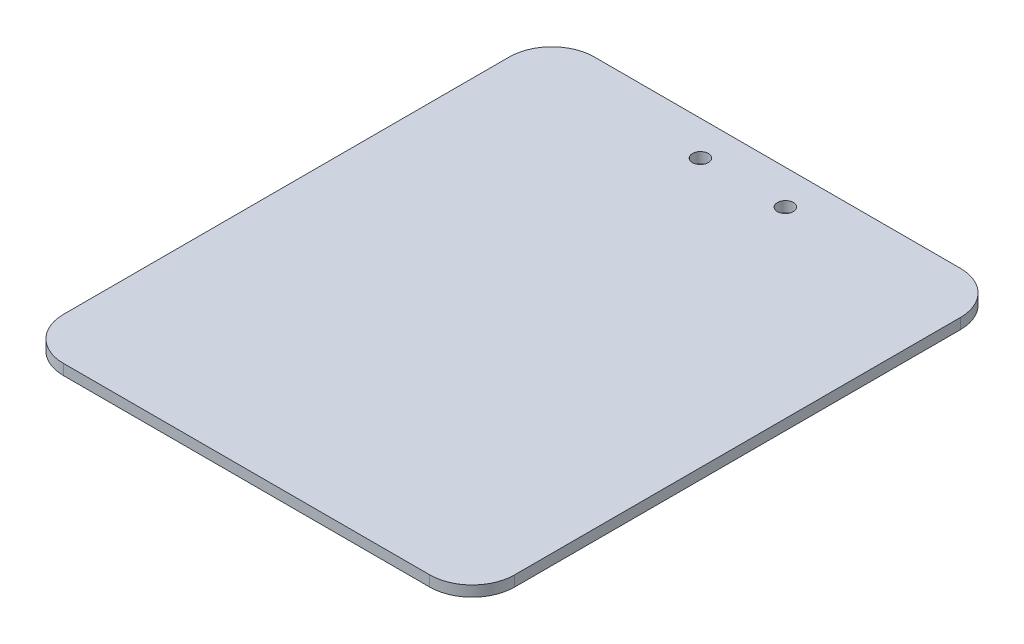
SolidWorks part; units mm, degrees
ref_plane "Front Plane" through (0, 0, 0) normal (0, 0, 1) x (1, 0, 0)
ref_plane "Top Plane" through (0, 0, 0) normal (0, 1, 0) x (1, 0, 0)
ref_plane "Right Plane" through (0, 0, 0) normal (1, 0, 0) x (0, 0, -1)
sketch "Sketch1" plane through (0, 0, 0) normal (0, 1, 0) x (1, 0, 0)
  line L0 (0, 50) -> (85, 50) construction
  line L1 (8, 0) -> (77, 0)
  line L2 (0, 8) -> (0, 92)
  line L3 (8, 100) -> (77, 100)
  line L4 (85, 8) -> (85, 92)
  line L5 (42.5, 100) -> (42.5, 0) construction
  circle A0 centre (50.5, 93.5) radius 1.5
  circle A1 centre (34.5, 93.5) radius 1.5
  arc A2 (8, 0) -> (0, 8) centre (8, 8) cw
  arc A3 (77, 0) -> (85, 8) centre (77, 8) ccw
  arc A4 (77, 100) -> (85, 92) centre (77, 92) cw
  arc A5 (0, 92) -> (8, 100) centre (8, 92) cw
  point P15 (0, 0)
  point P18 (85, 0)
  point P23 (0, 100)
  dimension "D3" = 3
  dimension "D6" = 8
  dimension "D1" = 85
  dimension "D2" = 100
  dimension "D4" = 6.5
  dimension "D5" = 8
extrude "Boss-Extrude1" add sketch "Sketch1" along normal blind 2
